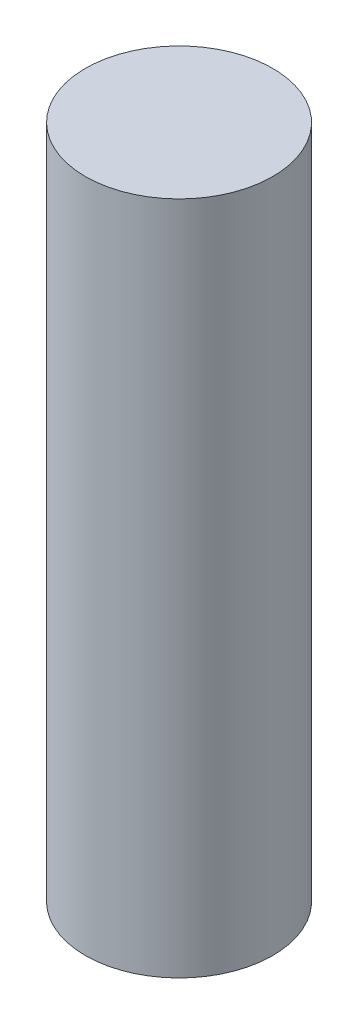
SolidWorks part; units mm, degrees
material "1060 Alloy"
ref_plane "Front Plane" through (0, 0, 0) normal (0, 0, 1) x (1, 0, 0)
ref_plane "Top Plane" through (0, 0, 0) normal (0, 1, 0) x (1, 0, 0)
ref_plane "Right Plane" through (0, 0, 0) normal (1, 0, 0) x (0, 0, -1)
sketch "Sketch1" plane through (0, 0, 0) normal (0, 1, 0) x (1, 0, 0)
  circle A0 centre (0, 0) radius 5
  dimension "D1" = 10
extrude "Boss-Extrude1" add sketch "Sketch1" along normal mid plane 36
